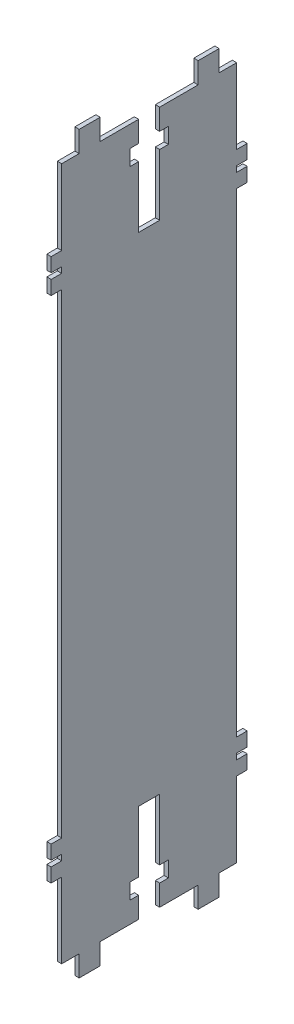
SolidWorks part; units mm, degrees
ref_plane "Front Plane" through (0, 0, 0) normal (0, 0, 1) x (1, 0, 0)
ref_plane "Top Plane" through (0, 0, 0) normal (0, 1, 0) x (1, 0, 0)
ref_plane "Right Plane" through (0, 0, 0) normal (1, 0, 0) x (0, 0, -1)
sketch "Sketch1" plane through (0, 0, 0) normal (1, 0, 0) x (0, 0, -1)
  line L0 (-60.5005, -173.902) -> (-60.5005, -177.902)
  line L1 (-67.7605, -173.902) -> (-60.5005, -173.902)
  line L2 (-67.7605, -164.2226) -> (-67.7605, -173.902)
  line L3 (-60.5005, -164.2226) -> (-67.7605, -164.2226)
  line L4 (-60.5005, 164.2175) -> (-60.5005, -164.2226)
  line L5 (-67.7605, 164.2175) -> (-60.5005, 164.2175)
  line L6 (-67.7605, 173.8986) -> (-67.7605, 164.2175)
  line L7 (-60.5005, 173.8986) -> (-67.7605, 173.8986)
  line L8 (-60.5005, 177.8987) -> (-60.5005, 173.8986)
  line L9 (-67.7605, 177.8987) -> (-60.5005, 177.8987)
  line L10 (-67.7605, 187.5797) -> (-67.7605, 177.8987)
  line L11 (-60.5005, 187.5797) -> (-67.7605, 187.5797)
  line L12 (-60.5005, 239.5797) -> (-60.5005, 187.5797)
  line L13 (-48.3998, 239.5797) -> (-60.5005, 239.5797)
  line L14 (-48.3998, 254.1015) -> (-48.3998, 239.5797)
  line L15 (-33.8815, 254.1015) -> (-48.3998, 254.1015)
  line L16 (-33.8815, 239.5797) -> (-33.8815, 254.1015)
  line L17 (-7.2693, 239.5797) -> (-33.8815, 239.5797)
  line L18 (-7.2693, 225.0631) -> (-7.2693, 239.5797)
  line L19 (-13.3169, 225.0631) -> (-7.2693, 225.0631)
  line L20 (-13.3169, 214.2148) -> (-13.3169, 225.0631)
  line L21 (-7.2693, 214.2148) -> (-13.3169, 214.2148)
  line L22 (-7.2693, 171.8218) -> (-7.2693, 214.2148)
  line L23 (7.2525, 171.8218) -> (-7.2693, 171.8218)
  line L24 (7.2525, 214.2148) -> (7.2525, 171.8218)
  line L25 (13.3102, 214.2148) -> (7.2525, 214.2148)
  line L26 (13.3102, 225.0631) -> (13.3102, 214.2148)
  line L27 (7.2525, 225.0631) -> (13.3102, 225.0631)
  line L28 (7.2525, 239.5797) -> (7.2525, 225.0631)
  line L29 (33.8798, 239.5797) -> (7.2525, 239.5797)
  line L30 (33.8798, 254.1015) -> (33.8798, 239.5797)
  line L31 (48.4014, 254.1015) -> (33.8798, 254.1015)
  line L32 (48.4014, 239.5797) -> (48.4014, 254.1015)
  line L33 (60.5005, 239.5797) -> (48.4014, 239.5797)
  line L34 (60.5005, 187.5797) -> (60.5005, 239.5797)
  line L35 (67.7604, 187.5797) -> (60.5005, 187.5797)
  line L36 (67.7604, 177.8987) -> (67.7604, 187.5797)
  line L37 (60.5005, 177.8987) -> (67.7604, 177.8987)
  line L38 (60.5005, 173.8986) -> (60.5005, 177.8987)
  line L39 (67.7604, 173.8986) -> (60.5005, 173.8986)
  line L40 (67.7604, 164.2175) -> (67.7604, 173.8986)
  line L41 (60.5005, 164.2175) -> (67.7604, 164.2175)
  line L42 (60.5005, -164.2226) -> (60.5005, 164.2175)
  line L43 (67.7604, -164.2226) -> (60.5005, -164.2226)
  line L44 (67.7604, -173.902) -> (67.7604, -164.2226)
  line L45 (60.5005, -173.902) -> (67.7604, -173.902)
  line L46 (60.5005, -177.902) -> (60.5005, -173.902)
  line L47 (67.7604, -177.902) -> (60.5005, -177.902)
  line L48 (67.7604, -187.5815) -> (67.7604, -177.902)
  line L49 (60.5005, -187.5815) -> (67.7604, -187.5815)
  line L50 (60.5005, -239.5814) -> (60.5005, -187.5815)
  line L51 (48.4014, -239.5814) -> (60.5005, -239.5814)
  line L52 (48.4014, -254.1014) -> (48.4014, -239.5814)
  line L53 (33.8798, -254.1014) -> (48.4014, -254.1014)
  line L54 (33.8798, -239.5814) -> (33.8798, -254.1014)
  line L55 (7.2525, -239.5814) -> (33.8798, -239.5814)
  line L56 (7.2525, -225.0631) -> (7.2525, -239.5814)
  line L57 (13.3102, -225.0631) -> (7.2525, -225.0631)
  line L58 (13.3102, -214.2031) -> (13.3102, -225.0631)
  line L59 (7.2525, -214.2031) -> (13.3102, -214.2031)
  line L60 (7.2525, -171.8219) -> (7.2525, -214.2031)
  line L61 (-7.2693, -171.8219) -> (7.2525, -171.8219)
  line L62 (-7.2693, -214.2031) -> (-7.2693, -171.8219)
  line L63 (-13.3169, -214.2031) -> (-7.2693, -214.2031)
  line L64 (-13.3169, -225.0631) -> (-13.3169, -214.2031)
  line L65 (-7.2693, -225.0631) -> (-13.3169, -225.0631)
  line L66 (-7.2693, -239.5814) -> (-7.2693, -225.0631)
  line L67 (-33.8815, -239.5814) -> (-7.2693, -239.5814)
  line L68 (-33.8815, -254.1014) -> (-33.8815, -239.5814)
  line L69 (-48.3998, -254.1014) -> (-33.8815, -254.1014)
  line L70 (-48.3998, -239.5814) -> (-48.3998, -254.1014)
  line L71 (-60.5005, -239.5814) -> (-48.3998, -239.5814)
  line L72 (-60.5005, -187.5815) -> (-60.5005, -239.5814)
  line L73 (-67.7605, -187.5815) -> (-60.5005, -187.5815)
  line L74 (-67.7605, -177.902) -> (-67.7605, -187.5815)
  line L75 (-60.5005, -177.902) -> (-67.7605, -177.902)
  dimension "D1" = 4
  dimension "D2" = 479.1612
  dimension "D3" = 52
  dimension "D4" = 9.6811
extrude "Boss-Extrude1" add sketch "Sketch1" along normal blind 3
